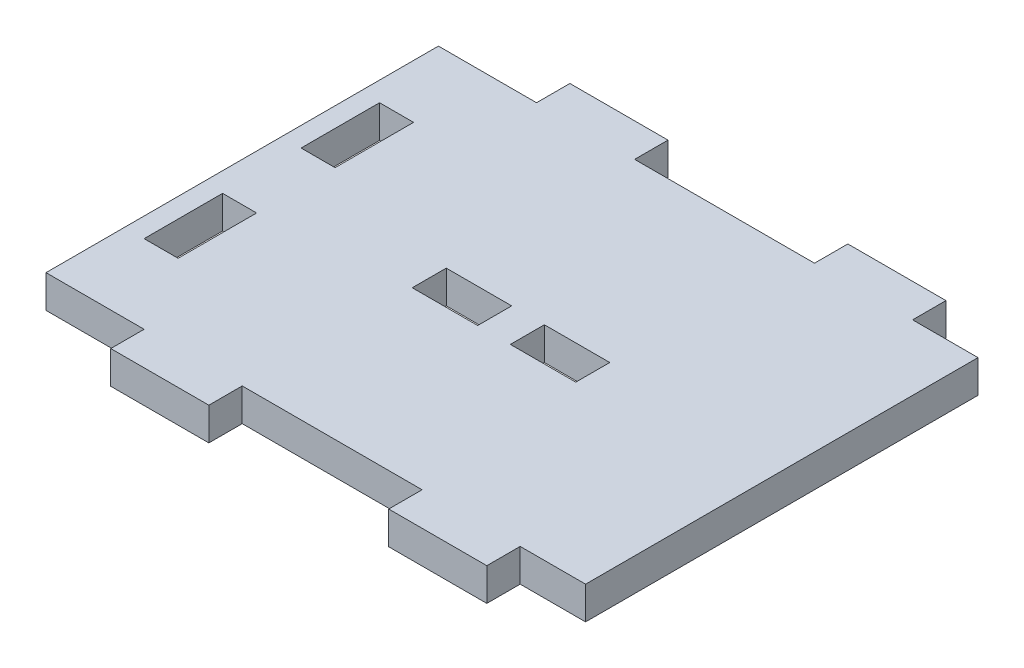
SolidWorks part; units mm, degrees
ref_plane "Front Plane" through (0, 0, 0) normal (0, 0, 1) x (1, 0, 0)
ref_plane "Top Plane" through (0, 0, 0) normal (0, 1, 0) x (1, 0, 0)
ref_plane "Right Plane" through (0, 0, 0) normal (1, 0, 0) x (0, 0, -1)
sketch "Sketch1" plane through (0, 0, 0) normal (0, 1, 0) x (1, 0, 0)
  line L0 (25, 30) -> (25, -30)
  line L1 (25, -30) -> (15, -30)
  line L2 (15, -30) -> (15, -35.1)
  line L3 (15, -35.1) -> (0, -35.1)
  line L4 (0, -35.1) -> (0, -30)
  line L5 (0, -30) -> (-27.5, -30)
  line L6 (-27.5, -30) -> (-27.5, -35.1)
  line L7 (-27.5, -35.1) -> (-42.5, -35.1)
  line L8 (-42.5, -35.1) -> (-42.5, -30)
  line L9 (-42.5, -30) -> (-57.5, -30)
  line L10 (-57.5, -30) -> (-57.5, 30)
  line L22 (-27.5, 1.2) -> (-17.5, 1.2)
  line L23 (-27.5, 1.2) -> (-27.5, -4)
  line L24 (-27.5, -4) -> (-17.5, -4)
  line L25 (-17.5, 1.2) -> (-17.5, -4)
  line L26 (-27.5, 1.2) -> (-17.5, -4) construction
  line L27 (-27.5, -4) -> (-17.5, 1.2) construction
  line L28 (-12.5, 1.2) -> (-2.5, 1.2)
  line L29 (-12.5, 1.2) -> (-12.5, -4)
  line L30 (-12.5, -4) -> (-2.5, -4)
  line L31 (-2.5, 1.2) -> (-2.5, -4)
  line L32 (-12.5, 1.2) -> (-2.5, -4) construction
  line L33 (-12.5, -4) -> (-2.5, 1.2) construction
  line L34 (25, 30) -> (15, 30)
  line L35 (15, 30) -> (15, 35.1)
  line L36 (15, 35.1) -> (0, 35.1)
  line L37 (0, 35.1) -> (0, 30)
  line L38 (0, 30) -> (-27.5, 30)
  line L39 (-27.5, 30) -> (-27.5, 35.1)
  line L40 (-27.5, 35.1) -> (-42.5, 35.1)
  line L41 (-42.5, 35.1) -> (-42.5, 30)
  line L42 (-42.5, 30) -> (-57.5, 30)
  line L44 (-54.5, -6) -> (-49.3, -6)
  line L45 (-54.5, -6) -> (-54.5, -18)
  line L46 (-54.5, -18) -> (-49.3, -18)
  line L47 (-49.3, -6) -> (-49.3, -18)
  line L48 (-54.5, -6) -> (-49.3, -18) construction
  line L49 (-54.5, -18) -> (-49.3, -6) construction
  line L50 (-54.5, 18) -> (-49.3, 18)
  line L51 (-49.3, 6) -> (-49.3, 18)
  line L52 (-54.5, 6) -> (-49.3, 6)
  line L53 (-54.5, 6) -> (-54.5, 18)
  point P0 (-22.5, -1.4)
  point P26 (-7.5, -1.4)
  dimension "D2" = 10
  dimension "D3" = 15
  dimension "D4" = 27.5
  dimension "D5" = 15
  dimension "D6" = 15
  dimension "D7" = 5.1
  dimension "D8" = 5.1
  dimension "D9" = 5.1
  dimension "D10" = 5.1
  dimension "D11" = 10
  dimension "D12" = 10
  dimension "D13" = 5.2
  dimension "D14" = 5.2
  dimension "D15" = 15
  dimension "D16" = 30
  dimension "D17" = 26
  dimension "D18" = 60
  dimension "D19" = 15
  dimension "D20" = 5.1
  dimension "D21" = 15
  dimension "D22" = 5.1
  dimension "D23" = 27.5
  dimension "D24" = 15
  dimension "D25" = 5.1
  dimension "D26" = 10
  dimension "D27" = 5.1
  dimension "D28" = 12
  dimension "D29" = 12
  dimension "D30" = 5.2
  dimension "D31" = 12
  dimension "D32" = 3
  dimension "D33" = 12
extrude "Boss-Extrude1" add sketch "Sketch1" along normal blind 5
